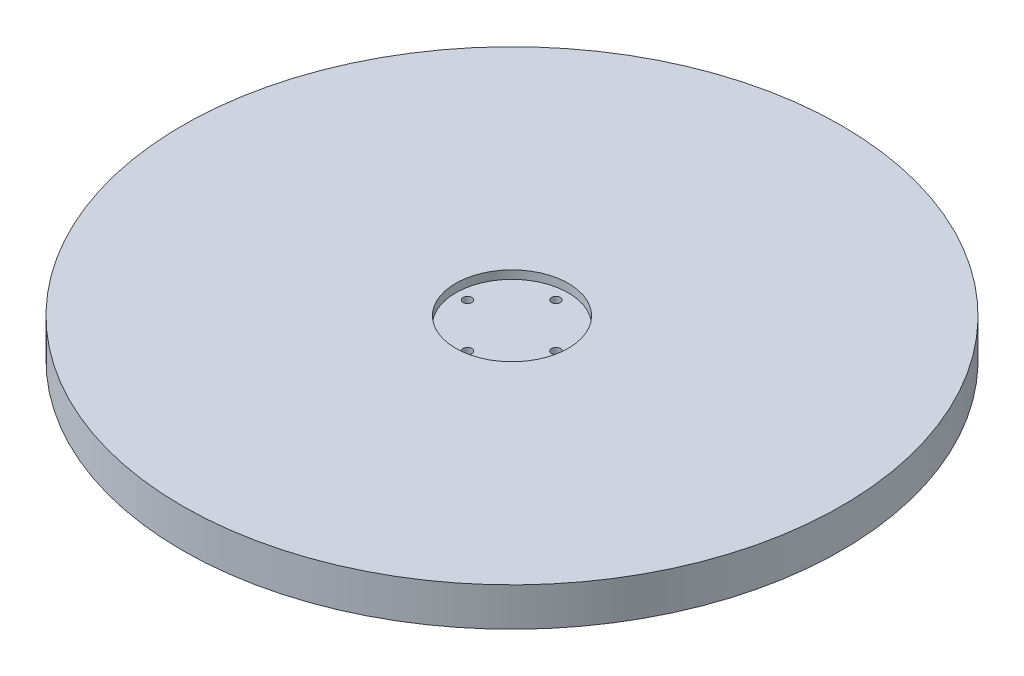
SolidWorks part; units mm, degrees
ref_plane "Front Plane" through (0, 0, 0) normal (0, 0, 1) x (1, 0, 0)
ref_plane "Top Plane" through (0, 0, 0) normal (0, 1, 0) x (1, 0, 0)
ref_plane "Right Plane" through (0, 0, 0) normal (1, 0, 0) x (0, 0, -1)
sketch "Sketch1" plane through (0, 0, 0) normal (0, 1, 0) x (1, 0, 0)
  circle A0 centre (0, 0) radius 60
  dimension "D1" = 120
extrude "Boss-Extrude1" add sketch "Sketch1" along normal blind 7
sketch "Sketch2" plane through (0, 7, 0) normal (0, 1, 0) x (1, 0, 0)
  circle A0 centre (0, 0) radius 10.25
  dimension "D1" = 20.5
extrude "Cut-Extrude1" cut sketch "Sketch2" against normal blind 1.5
hole_wizard "Tap Drill for M2x0.4 Tap1" positions "Sketch6" profile "Sketch7" hole size "M2x0.4" standard "ANSI Metric" end condition through all
sketch "Sketch6" plane through (0, 5.5, 0) normal (0, 1, 0) x (1, 0, 0)
  point P0 (0, 8)
  dimension "D1" = 8
sketch "Sketch7" plane through (0, 5.5, -8) normal (1, 0, 0) x (0, 0, 1)
  line L0 (0, 0) -> (0, 5.5)
  line L1 (0, 5.5) -> (0.8, 5.5)
  line L2 (0.8, 5.5) -> (0.8, 0)
  line L5 (0.8, 0) -> (0, 0)
  line L11 (0, -6.35) -> (0, 107.95) construction
  dimension "Thru Hole Dia." = 1.6
  dimension "Thru Hole Depth" = 5.5
pattern_circular "CirPattern1" count 4 over 360 about axis through (0, 0, 0.049) along (0, 1, 0) of "Tap Drill for M2x0.4 Tap1"
sketch "Sketch8" plane through (0, 0, 0) normal (0, -1, 0) x (1, 0, 0)
  circle A0 centre (0, 0) radius 35
  circle A1 centre (0, 0) radius 25
  dimension "D1" = 70
  dimension "D2" = 50
extrude "Cut-Extrude-Thin1" cut sketch "Sketch8" against normal blind 4 thin contours A0
